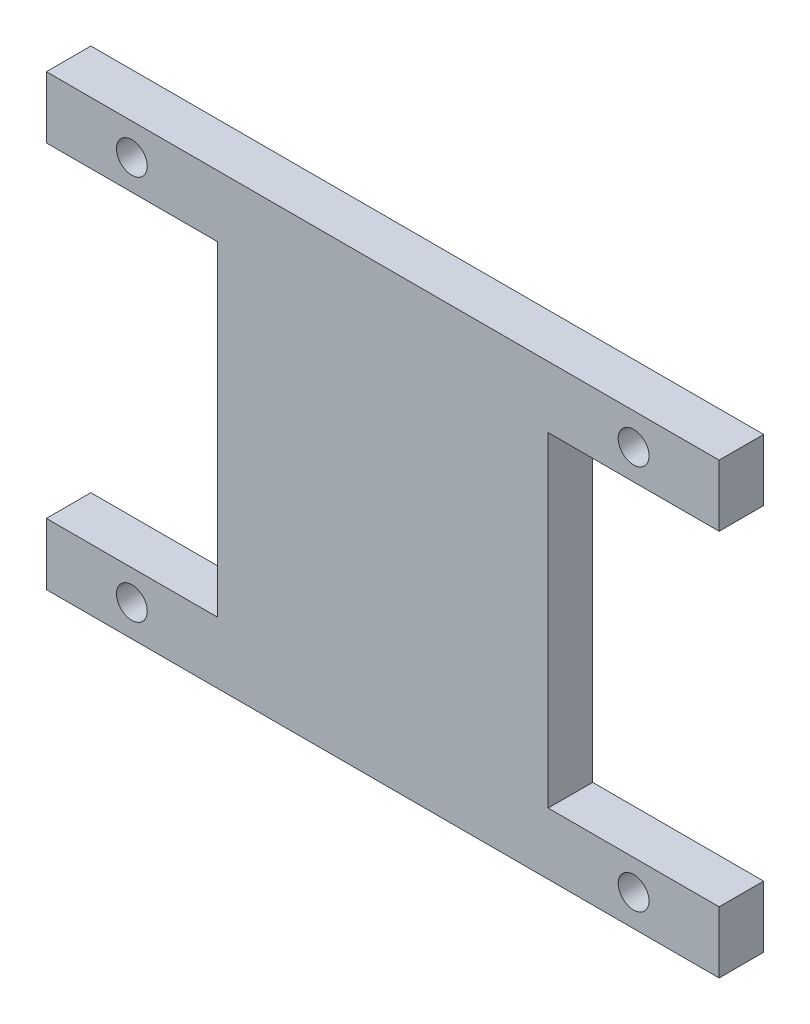
SolidWorks part; units mm, degrees
ref_plane "Front Plane" through (0, 0, 0) normal (0, 0, 1) x (1, 0, 0)
ref_plane "Top Plane" through (0, 0, 0) normal (0, 1, 0) x (1, 0, 0)
ref_plane "Right Plane" through (0, 0, 0) normal (1, 0, 0) x (0, 0, -1)
sketch "Sketch1" plane through (0, 0, 0) normal (0, 0, 1) x (1, 0, 0)
  line L1 (0, 0) -> (48, 0)
  line L2 (0, 0) -> (0, 32)
  line L3 (0, 32) -> (48, 32)
  line L4 (48, 0) -> (48, 32)
  line L5 (0, 27.6) -> (12.2, 27.6)
  line L6 (0, 27.6) -> (0, 4.4)
  line L7 (0, 4.4) -> (12.2, 4.4)
  line L8 (12.2, 27.6) -> (12.2, 4.4)
  line L9 (48, 27.6) -> (35.8, 27.6)
  line L10 (48, 27.6) -> (48, 4.4)
  line L11 (48, 4.4) -> (35.8, 4.4)
  line L12 (35.8, 27.6) -> (35.8, 4.4)
  circle A0 centre (6.1, 29.75) radius 1.1
  circle A1 centre (6.1, 2.25) radius 1.1
  circle A2 centre (41.9, 29.75) radius 1.1
  circle A3 centre (41.9, 2.25) radius 1.1
  dimension "D8" = 2.2
  dimension "D9" = 2.2
  dimension "D15" = 2.2
  dimension "D18" = 2.2
  dimension "D1" = 32
  dimension "D2" = 48
  dimension "D3" = 23.2
  dimension "D4" = 4.4
  dimension "D5" = 12.2
  dimension "D6" = 27.5
  dimension "D7" = 6.1
  dimension "D10" = 2.25
  dimension "D11" = 23.2
  dimension "D12" = 12.2
  dimension "D13" = 6.1
  dimension "D14" = 4.4
  dimension "D16" = 2.25
  dimension "D17" = 27.5
extrude "Boss-Extrude1" add sketch "Sketch1" along normal blind 3.175 contours L12 L9 L4 L3 L2 L5 L8 L7 L1 L11 A3 A2 A1 A0
